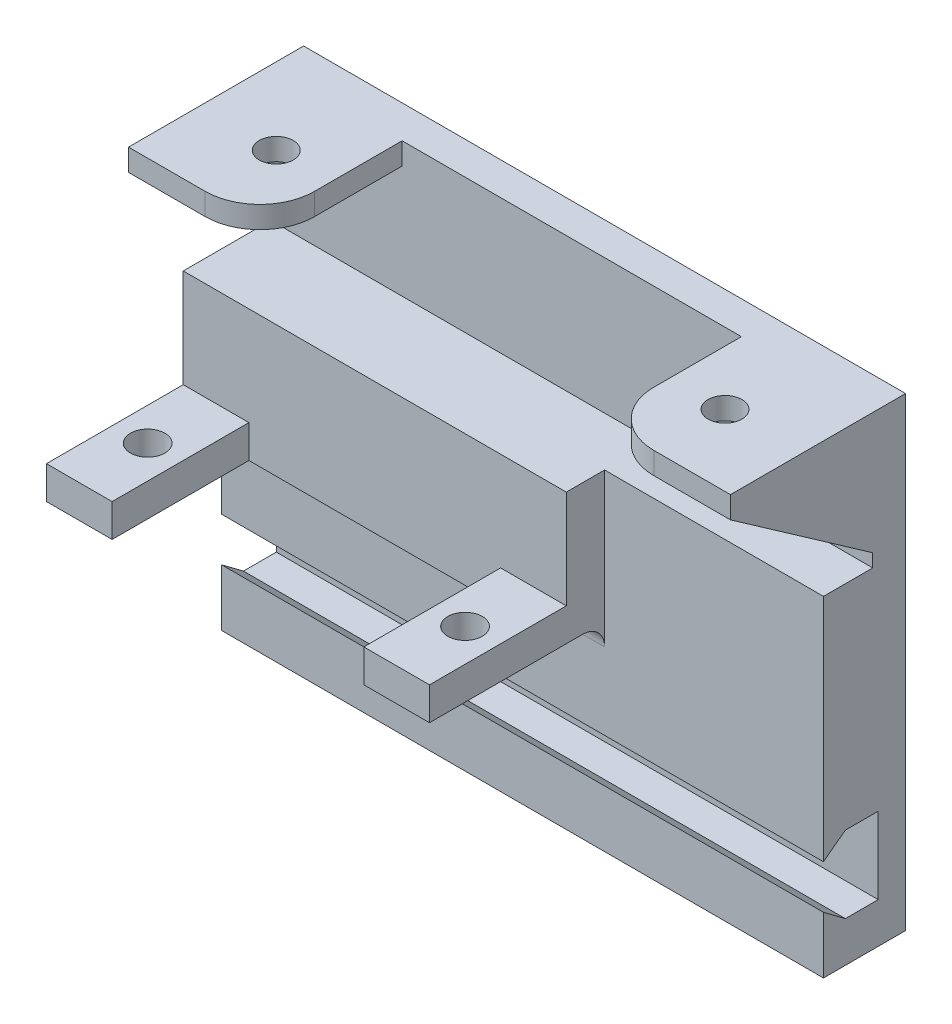
SolidWorks part; units mm, degrees
ref_plane "Front Plane" through (0, 0, 0) normal (0, 0, 1) x (1, 0, 0)
ref_plane "Top Plane" through (0, 0, 0) normal (0, 1, 0) x (1, 0, 0)
ref_plane "Right Plane" through (0, 0, 0) normal (1, 0, 0) x (0, 0, -1)
sketch "Sketch1" plane through (0, 0, 0) normal (0, 0, 1) x (1, 0, 0)
  line L0 (0, 36.5672) -> (0, -36.8059) construction
  line L1 (-27.5, 21.25) -> (27.5, 21.25)
  line L2 (-27.5, -21.25) -> (27.5, -21.25)
  line L3 (-40.564, 0) -> (45.4555, 0) construction
  line L4 (-27.5, 21.25) -> (-27.5, -21.25)
  line L5 (27.5, 21.25) -> (27.5, -21.25)
  dimension "D1" = 55
  dimension "D2" = 42.5
extrude "Boss-Extrude1" add sketch "Sketch1" along normal blind 23.5
sketch "Sketch2" plane through (27.5, 0, 0) normal (1, 0, 0) x (0, 0, -1)
  line L0 (-3, 21.25) -> (-3, 8.95)
  line L1 (-23.5, 21.25) -> (0, 21.25) construction
  line L2 (-3, 8.95) -> (-11, 8.95)
  line L3 (-11, 8.95) -> (-11, -0.05)
  line L4 (-11, -0.05) -> (-23.5, -0.05)
  line L5 (-23.5, -21.25) -> (-23.5, 21.25) construction
  line L10 (-5.5, -10.55) -> (-2.5, -10.55)
  line L11 (-2.5, -10.55) -> (-2.5, -17.55)
  line L12 (-2.5, -17.55) -> (-5.5, -17.55)
  line L16 (-7.5, -21.25) -> (-33.2417, -21.25)
  line L17 (-33.2417, -21.25) -> (-33.2417, 21.25)
  line L18 (-33.2417, 21.25) -> (-3, 21.25)
  line L19 (-23.5, -0.05) -> (-23.5, -3.05)
  line L20 (-23.5, -3.05) -> (-9.5, -3.05)
  line L21 (-7.5, -5.05) -> (-7.5, -12.05)
  line L22 (-20.1577, -14.05) -> (-2.2551, -14.05) construction
  line L23 (-7.5, -16.05) -> (-7.5, -21.25)
  line L24 (-5.5, -10.55) -> (-7.5, -12.05)
  line L25 (-5.5, -17.55) -> (-7.5, -16.05)
  arc A0 (-9.5, -3.05) -> (-7.5, -5.05) centre (-9.5, -5.05) cw
  point P20 (-7.5, -3.05)
  dimension "D13" = 2
  dimension "D1" = 12.3
  dimension "D2" = 3
  dimension "D3" = 8
  dimension "D4" = 9
  dimension "D5" = 3
  dimension "D6" = 9
  dimension "D7" = 5
  dimension "D8" = 4
  dimension "D9" = 3
  dimension "D10" = 3
  dimension "D11" = 7
  dimension "D12" = 16
extrude "Cut-Extrude1" cut sketch "Sketch2" against normal through all both
sketch "Sketch3" plane through (0, 0, 0) normal (0, 1, 0) x (1, 0, 0)
  line L3 (7.5, -10.9959) -> (7.5, -23.5)
  line L4 (-27.5, -23.5) -> (27.5, -23.5) construction
  line L5 (7.5, -23.5) -> (27.5, -23.5)
  line L6 (27.5, -23.5) -> (27.5, -10.9935)
  line L8 (7.5, -10.9959) -> (7.5, -7.5)
  line L9 (-27.5, -7.5) -> (27.5, -7.5) construction
  line L10 (7.5, -7.5) -> (27.5, -7.5)
  line L11 (27.5, -7.5) -> (27.5, -10.9935)
extrude "Cut-Extrude2" cut sketch "Sketch3" against normal through all both and the other way through all
sketch "Sketch4" plane through (0, 0, 0) normal (0, 1, 0) x (1, 0, 0)
  line L0 (-21.5, -23.5) -> (-21.5, -11)
  line L1 (-27.5, -23.5) -> (7.5, -23.5) construction
  line L2 (-27.5, -11) -> (7.5, -11) construction
  line L3 (-21.5, -11) -> (1.5, -11)
  line L4 (1.5, -11) -> (1.5, -23.5)
  line L5 (1.5, -23.5) -> (-21.5, -23.5)
  line L6 (-27.5, -23.5) -> (-27.5, -11) construction
  dimension "D1" = 23
  dimension "D2" = 6
extrude "Cut-Extrude3" cut sketch "Sketch4" against normal through all both
sketch "Sketch5" plane through (0, -0.05, 0) normal (0, 1, 0) x (1, 0, 0)
  line L0 (-24.5, -23.5) -> (-24.5, -10.5296) construction
  line L1 (-27.5, -23.5) -> (-21.5, -23.5) construction
  line L2 (4.5, -23.5) -> (4.5, -11) construction
  line L3 (1.5, -23.5) -> (7.5, -23.5) construction
  line L4 (1.5, -11) -> (7.5, -11) construction
  line L5 (-21.5, -17.25) -> (-27.5, -17.25) construction
  line L6 (-21.5, -23.5) -> (-21.5, -11) construction
  line L7 (-27.5, -23.5) -> (-27.5, -11) construction
  line L8 (1.5, -17.25) -> (7.5, -17.25) construction
  line L9 (1.5, -11) -> (1.5, -23.5) construction
  line L10 (7.5, -23.5) -> (7.5, -11) construction
  circle A0 centre (-24.5, -17.25) radius 1.575
  circle A1 centre (4.5, -17.25) radius 1.575
  dimension "D1" = 3.15
  dimension "D2" = 3.15
extrude "Cut-Extrude4" cut sketch "Sketch5" against normal through all both
sketch "Sketch6" plane through (0, 21.25, 0) normal (0, 1, 0) x (1, 0, 0)
  line L0 (-27.5, -3) -> (-27.5, -16)
  line L1 (-27.5, -11) -> (-27.5, -3) construction
  line L2 (-27.5, -16) -> (-20.5, -16)
  line L3 (-15.5, -11) -> (-15.5, -3)
  line L4 (-27.5, -3) -> (27.5, -3) construction
  line L5 (-15.5, -3) -> (-27.5, -3)
  line L7 (0, -16.8041) -> (0, 8.3955) construction
  line L8 (15.5, -3) -> (27.5, -3)
  line L9 (15.5, -11) -> (15.5, -3)
  line L10 (27.5, -16) -> (20.5, -16)
  line L11 (27.5, -3) -> (27.5, -16)
  arc A0 (-20.5, -16) -> (-15.5, -11) centre (-20.5, -11) ccw
  arc A1 (20.5, -16) -> (15.5, -11) centre (20.5, -11) cw
  dimension "D3" = 5
  dimension "D1" = 13
  dimension "D2" = 12
extrude "Boss-Extrude2" add sketch "Sketch6" against normal blind 2
sketch "Sketch7" plane through (27.5, 0, 0) normal (1, 0, 0) x (0, 0, -1)
  line L0 (-3, 19.25) -> (-3, 10.1505)
  line L1 (-3, 8.95) -> (-3, 19.25) construction
  line L2 (-3, 10.1505) -> (-16, 19.25)
  line L3 (-16, 19.25) -> (-3, 19.25)
extrude "Boss-Extrude3" add sketch "Sketch7" against normal blind 2
sketch "Sketch8" plane through (0, 0, 0) normal (0, 0, 1) x (1, 0, 0)
  line L0 (0, -22.474) -> (0, 22.1763) construction
sketch "Sketch9" plane through (-27.5, 0, 0) normal (-1, 0, 0) x (0, 0, 1)
  line L0 (16, 19.25) -> (3, 10.1505)
  line L1 (3, 10.1505) -> (3, 19.25)
  line L2 (3, 19.25) -> (16, 19.25)
extrude "Boss-Extrude4" add sketch "Sketch9" against normal blind 2
sketch "Sketch11" plane through (0, 21.25, 0) normal (0, 1, 0) x (1, 0, 0)
  line L0 (0, 3.699) -> (0, -16.1257) construction
  line L1 (-25.9567, -9.5) -> (27.5, -9.5) construction
  line L2 (27.5, -16) -> (27.5, 0) construction
  line L3 (27.5, 0) -> (-27.5, 0) construction
  line L4 (-27.5, -16) -> (-27.5, 0) construction
  circle A0 centre (-20.5, -9.5) radius 1.55
  circle A1 centre (20.5, -9.5) radius 1.55
  point P13 (0, 0)
  dimension "D2" = 3.1
  dimension "D1" = 9.5
  dimension "D3" = 7
extrude "Cut-Extrude5" cut sketch "Sketch11" against normal blind 2
